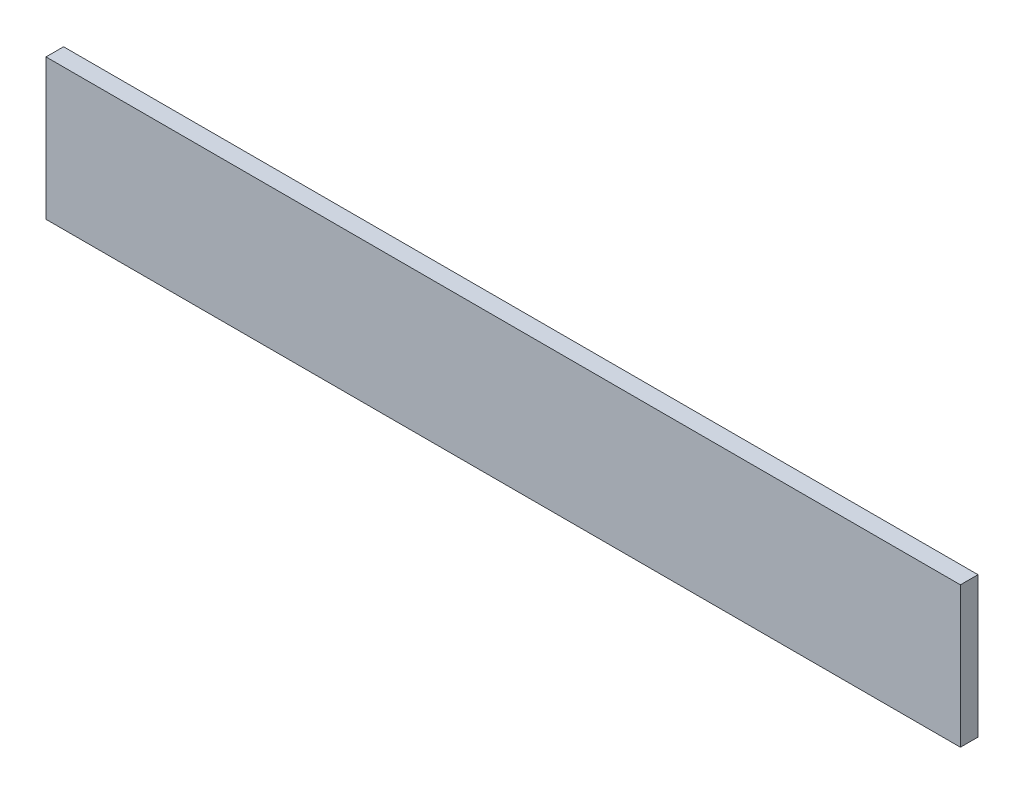
SolidWorks part; units mm, degrees
ref_plane "정면" through (0, 0, 0) normal (0, 0, 1) x (1, 0, 0)
ref_plane "윗면" through (0, 0, 0) normal (0, 1, 0) x (1, 0, 0)
ref_plane "우측면" through (0, 0, 0) normal (1, 0, 0) x (0, 0, -1)
sketch "스케치1" plane through (0, 0, 0) normal (0, 0, 1) x (1, 0, 0)
  line L0 (20, -7) -> (20, -10) construction
  line L1 (0, 0) -> (40, 0)
  line L2 (0, 0) -> (0, -40)
  line L3 (0, -40) -> (40, -40)
  line L4 (40, 0) -> (40, -40)
  line L5 (17, -10) -> (23, -10)
  line L6 (17, -10) -> (17, -31)
  line L7 (17, -31) -> (23, -31)
  line L8 (23, -10) -> (23, -31)
  line L9 (19, -10) -> (21, -10)
  line L10 (19, -10) -> (19, -7)
  line L11 (19, -7) -> (21, -7)
  line L12 (21, -10) -> (21, -7)
  line L13 (20, -10) -> (20, -40) construction
  line L14 (5, 5) -> (35, 5) construction
  line L15 (5, 5) -> (5, -10)
  line L16 (5, -10) -> (10, -10)
  line L17 (10, -10) -> (10, 5)
  line L18 (30, 5) -> (30, -35)
  line L19 (30, -35) -> (35, -35)
  line L20 (35, -35) -> (35, 5)
  line L22 (4, -4) -> (30, -4)
  line L23 (4, -4) -> (4, -8)
  line L24 (4, -8) -> (30, -8)
  line L25 (30, -4) -> (30, -8)
  line L26 (18, -4) -> (22, -4)
  line L27 (18, -4) -> (18, -9)
  line L28 (18, -9) -> (22, -9)
  line L29 (22, -4) -> (22, -9)
  arc A0 (10, 5) -> (30, 5) centre (20, 5) cw
  arc A1 (5, 5) -> (35, 5) centre (20, 5) cw
  point P30 (20, -9)
  dimension "D7" = 5
  dimension "D8" = 10
  dimension "D1" = 2
  dimension "D2" = 3
  dimension "D3" = 21
  dimension "D4" = 6
  dimension "D5" = 40
  dimension "D6" = 40
  dimension "D9" = 40
  dimension "D10" = 15
  dimension "D11" = 10
  dimension "D12" = 5
  dimension "D13" = 4
  dimension "D14" = 4
  dimension "D15" = 5
  dimension "D16" = 2
  dimension "D17" = 1
extrude "보스-돌출1" add sketch "스케치1" along normal blind 0.5 contours L24 L25 L22 L23
